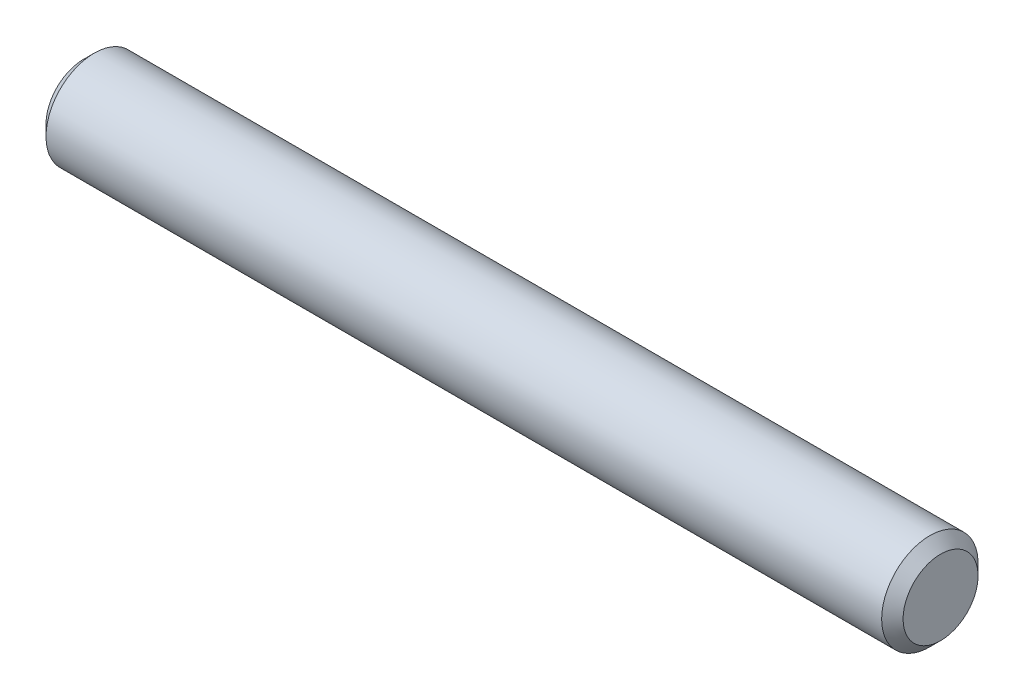
SolidWorks part; units mm, degrees
ref_plane "前视基准面" through (0, 0, 0) normal (0, 0, 1) x (1, 0, 0)
ref_plane "上视基准面" through (0, 0, 0) normal (0, 1, 0) x (1, 0, 0)
ref_plane "右视基准面" through (0, 0, 0) normal (1, 0, 0) x (0, 0, -1)
sketch "草图1" plane through (0, 0, 0) normal (0, 0, 1) x (1, 0, 0)
  line L0 (-6.3202, 0) -> (6.9944, 0) construction
  line L1 (-5.3427, 0) -> (-5.3427, 0.9)
  line L2 (-5.3427, 0.9) -> (10.6573, 0.9)
  line L3 (10.6573, 0.9) -> (10.6573, 0)
  line L4 (-5.3427, 0) -> (10.6573, 0)
  dimension "D1" = 16
  dimension "D2" = 0.9
revolve "旋转1" add sketch "草图1" angle 360 about L0
chamfer "倒角1" distance 0.2 angle 45 2 edges at (-5.3427, 0, 0.9) (10.6573, 0, 0.9)
